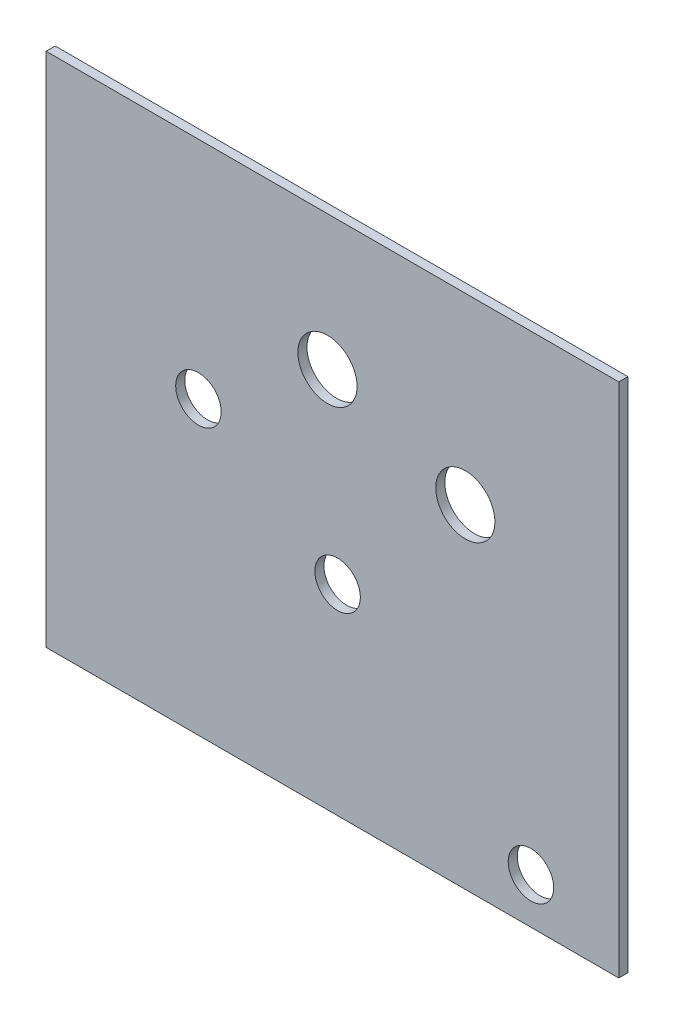
SolidWorks part; units mm, degrees
ref_plane "Plane1" through (0, 0, 0) normal (0, 0, 1) x (1, 0, 0)
ref_plane "Plane2" through (0, 0, 0) normal (0, 1, 0) x (1, 0, 0)
ref_plane "Plane3" through (0, 0, 0) normal (1, 0, 0) x (0, 0, -1)
sketch "Sketch1" plane through (0, 0, 0) normal (0, 0, 1) x (1, 0, 0)
  line L1 (0, 0) -> (-125.8704, 0)
  line L2 (0, 0) -> (0, 113.4818)
  line L3 (0, 113.4818) -> (-125.8704, 113.4818)
  line L4 (-125.8704, 0) -> (-125.8704, 113.4818)
extrude "Boss-Extrude1" add sketch "Sketch1" along normal blind 2
hole_wizard "CBORE for M5 Hex Head Bolt1" positions "Sketch2" profile "Sketch3" counterbore size "M5" standard "Synventive" end condition through all
sketch "Sketch2" plane through (0, 0, 0) normal (0, 0, -1) x (-1, 0, 0)
  point P0 (33.7296, 73.2178)
  point P2 (64.0284, 83.838)
sketch "Sketch3" plane through (-33.7296, 73.2178, 0) normal (1, 0, 0) x (0, 1, 0)
  line L0 (0, 0) -> (0, 2)
  line L1 (0, 2) -> (2.75, 2)
  line L3 (2.75, 2) -> (2.75, 3.5)
  line L4 (2.75, 3.5) -> (6.5, 3.5)
  line L5 (6.5, 3.5) -> (6.5, 0)
  line L7 (6.5, 0) -> (0, 0)
  line L11 (0, -6.35) -> (0, 107.95) construction
  dimension "Thru Hole Dia." = 5.5
  dimension "Thru Hole Depth" = 2
  dimension "C'Bore Dia." = 13
  dimension "C'Bore Depth" = 3.5
sketch "Sketch4" plane through (0, 0, 0) normal (0, 0, -1) x (-1, 0, 0)
  line L0 (125.8704, 0) -> (0, 0) construction
  circle A0 centre (19.3049, 10) radius 5
  circle A1 centre (61.8107, 44.0501) radius 5
  circle A2 centre (92.3969, 64.0501) radius 5
  dimension "D1" = 10
  dimension "D2" = 20
  dimension "D3" = 10
extrude "Cut-Extrude1" cut sketch "Sketch4" against normal blind 2
